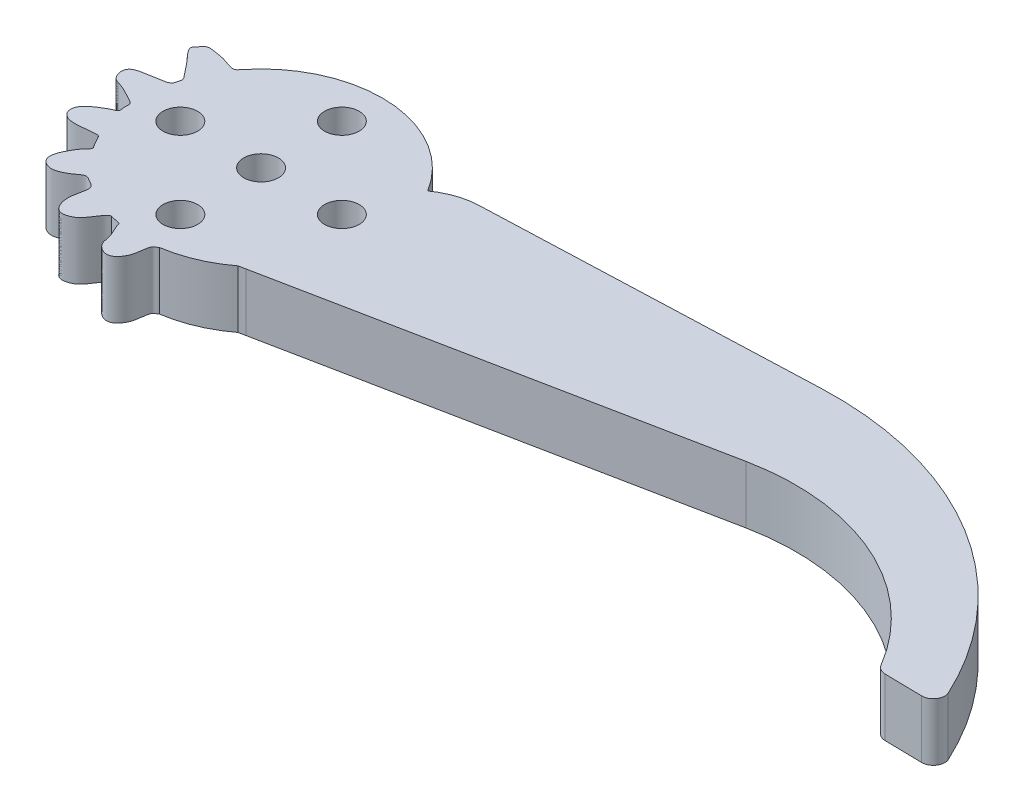
SolidWorks part; units mm, degrees
material "Thornel Mat VMA"
ref_plane "前视基准面" through (0, 0, 0) normal (0, 0, 1) x (1, 0, 0)
ref_plane "上视基准面" through (0, 0, 0) normal (0, 1, 0) x (1, 0, 0)
ref_plane "右视基准面" through (0, 0, 0) normal (1, 0, 0) x (0, 0, -1)
sketch "草图1" plane through (0, 0, 0) normal (0, 1, 0) x (1, 0, 0)
  line L0 (-21.0651, -6.9034) -> (15.0591, 0.323)
  line L1 (-39.2243, 6.1638) -> (-38.0931, 4.752)
  line L2 (-36.2478, 7.8215) -> (-36.3763, 7.6689)
  line L3 (12.8477, 9.059) -> (-15.7391, 7.9639)
  line L4 (37.0468, -9.61) -> (40.2704, -9.6677)
  arc A0 (-26.404, -9.0395) -> (-21.6294, -7.0162) centre (-27.9866, 1.3406) ccw
  arc A1 (-30.8811, -8.7526) -> (-29.9513, -8.974) centre (-27.9866, 1.3406) ccw
  arc A2 (-37.3561, -3.3988) -> (-36.7558, -4.4345) centre (-27.9866, 1.3406) ccw
  arc A3 (-38.0056, 4.4822) -> (-38.1702, 3.8986) centre (-27.9866, 1.3406) ccw
  arc A4 (-19.0327, 6.8249) -> (-36.2478, 7.8215) centre (-27.9866, 1.3406) ccw
  arc A5 (-15.7391, 7.9639) -> (-19.0327, 6.8249) centre (-15.5094, 1.9683) ccw
  arc A6 (41.2369, -8.3515) -> (12.8477, 9.059) centre (13.9962, -20.919) ccw
  arc A7 (40.2704, -9.6677) -> (41.2369, -8.3515) centre (40.2883, -8.6679) ccw
  arc A8 (36.2036, -9.1187) -> (37.0468, -9.61) centre (37.0647, -8.6102) ccw
  arc A9 (36.2036, -9.1187) -> (15.0591, 0.323) centre (18.9822, -19.2884) ccw
  ellipse E0 centre (-38.7365, 4.3843) end of major axis (-39.385, 4.0256) minor radius 0.7149 (-38.0056, 4.4822) -> (-38.0931, 4.752) ccw
  spline S0 degree 3 poles (-21.6294, -7.0162) (-21.4401, -6.9711) (-21.2528, -6.9333) (-21.0651, -6.9034) knots 0 0 0 0 1 1 1 1 weights 1 1 1 1
  spline S1 degree 3 poles (-29.9513, -8.974) (-29.9474, -9.0011) (-29.9366, -9.0585) (-29.9134, -9.15) (-29.8843, -9.245) (-29.8509, -9.3408) (-29.8138, -9.4371) (-29.7743, -9.5317) (-29.7328, -9.6252) (-29.6904, -9.7164) (-29.6478, -9.8051) (-29.6061, -9.8908) (-29.5656, -9.9745) (-29.5271, -10.0566) (-29.4927, -10.1347) (-29.4632, -10.2082) (-29.4382, -10.2778) (-29.4162, -10.3475) (-29.3964, -10.4191) (-29.3787, -10.4925) (-29.3607, -10.5762) (-29.3436, -10.6642) (-29.3261, -10.7549) (-29.309, -10.8384) (-29.2903, -10.9194) (-29.2689, -10.9978) (-29.244, -11.0736) (-29.2146, -11.1472) (-29.1798, -11.2185) (-29.1395, -11.2873) (-29.0934, -11.3536) (-29.0384, -11.4214) (-28.9661, -11.4975) (-28.8737, -11.5784) (-28.7599, -11.6594) (-28.6404, -11.7266) (-28.518, -11.7789) (-28.4, -11.8151) (-28.2935, -11.8345) (-28.1998, -11.8406) (-28.1193, -11.8375) (-28.0403, -11.8258) (-27.963, -11.8055) (-27.8815, -11.7747) (-27.7968, -11.7317) (-27.7101, -11.6755) (-27.625, -11.6083) (-27.5493, -11.5366) (-27.4832, -11.4636) (-27.4277, -11.3948) (-27.376, -11.3232) (-27.3259, -11.2467) (-27.2833, -11.1757) (-27.2476, -11.1119) (-27.2188, -11.0579) (-27.1921, -11.0048) (-27.1672, -10.9523) (-27.1443, -10.9) (-27.1231, -10.847) (-27.1014, -10.7865) (-27.0824, -10.7246) (-27.0654, -10.6594) (-27.0517, -10.5993) (-27.0385, -10.5338) (-27.0256, -10.4629) (-27.013, -10.3866) (-27.0005, -10.3055) (-26.988, -10.2202) (-26.975, -10.1284) (-26.9612, -10.0316) (-26.9466, -9.9318) (-26.9315, -9.8349) (-26.9158, -9.7422) (-26.8992, -9.6552) (-26.8817, -9.5749) (-26.8629, -9.5021) (-26.8428, -9.4373) (-26.821, -9.3808) (-26.7975, -9.3323) (-26.7718, -9.2916) (-26.7439, -9.2577) (-26.7135, -9.2296) (-26.6802, -9.206) (-26.6438, -9.1852) (-26.604, -9.1652) (-26.5606, -9.1436) (-26.5131, -9.1179) (-26.4613, -9.085) (-26.4237, -9.0562) (-26.404, -9.0395) knots 0 0 0 0 0.013505 0.02701 0.039991 0.053322 0.066303 0.079285 0.092266 0.105447 0.118428 0.131409 0.144391 0.157372 0.170353 0.181624 0.192111 0.202598 0.213086 0.223573 0.23406 0.248243 0.260115 0.271987 0.283859 0.295731 0.307654 0.319769 0.331885 0.344001 0.356116 0.368232 0.382792 0.402054 0.421317 0.443013 0.461451 0.47974 0.498046 0.510723 0.52339 0.536057 0.548724 0.56146 0.577383 0.593228 0.609073 0.626493 0.63938 0.65177 0.664159 0.676549 0.69008 0.699149 0.708218 0.717287 0.726355 0.735424 0.744493 0.753562 0.765524 0.773304 0.781085 0.788865 0.796646 0.804426 0.812207 0.819987 0.827768 0.836464 0.845107 0.853712 0.862317 0.870922 0.879527 0.888133 0.896738 0.905343 0.913948 0.922553 0.931159 0.939764 0.948369 0.956974 0.965579 0.974184 0.98279 0.991395 1 1 1 1 weights 1 1 1 1 1 1 1 1 1 1 1 1 1 1 1 1 1 1 1 1 1 1 1 1 1 1 1 1 1 1 1 1 1 1 1 1 1 1 1 1 1 1 1 1 1 1 1 1 1 1 1 1 1 1 1 1 1 1 1 1 1 1 1 1 1 1 1 1 1 1 1 1 1 1 1 1 1 1 1 1 1 1 1 1 1 1 1 1 1 1
  spline S2 degree 3 poles (-36.7558, -4.4345) (-36.7576, -4.4486) (-36.7635, -4.4864) (-36.7767, -4.54) (-36.7973, -4.5932) (-36.8227, -4.6397) (-36.8528, -4.682) (-36.8873, -4.7226) (-36.9259, -4.7636) (-36.9683, -4.8067) (-37.0141, -4.8535) (-37.063, -4.905) (-37.1145, -4.9622) (-37.1683, -5.0256) (-37.2238, -5.0953) (-37.2805, -5.1714) (-37.338, -5.2534) (-37.3963, -5.3416) (-37.4542, -5.4342) (-37.5123, -5.5317) (-37.5667, -5.6275) (-37.6169, -5.719) (-37.6617, -5.8029) (-37.7029, -5.8824) (-37.7412, -5.958) (-37.7763, -6.0296) (-37.8084, -6.0968) (-37.8374, -6.1601) (-37.8673, -6.2284) (-37.8944, -6.2949) (-37.9192, -6.3615) (-37.9396, -6.4218) (-37.9581, -6.4827) (-37.9749, -6.5449) (-37.99, -6.6096) (-38.0034, -6.6774) (-38.0151, -6.7524) (-38.0235, -6.833) (-38.0269, -6.9174) (-38.024, -6.9999) (-38.0143, -7.08) (-37.9963, -7.1615) (-37.9678, -7.2447) (-37.9265, -7.3286) (-37.8735, -7.4082) (-37.8116, -7.4801) (-37.7428, -7.544) (-37.6692, -7.6) (-37.5899, -7.6499) (-37.5038, -7.6949) (-37.4219, -7.7299) (-37.3467, -7.7566) (-37.2814, -7.7761) (-37.2167, -7.7916) (-37.1525, -7.8031) (-37.0886, -7.8105) (-37.0244, -7.8135) (-36.9589, -7.8121) (-36.8913, -7.8061) (-36.8204, -7.7955) (-36.7454, -7.7801) (-36.6652, -7.7598) (-36.579, -7.7342) (-36.4863, -7.7028) (-36.3891, -7.666) (-36.2887, -7.6238) (-36.1869, -7.5767) (-36.0837, -7.5241) (-35.9804, -7.4666) (-35.8778, -7.4046) (-35.7769, -7.3392) (-35.6785, -7.2715) (-35.5816, -7.2018) (-35.4924, -7.1358) (-35.4111, -7.0757) (-35.3392, -7.0235) (-35.2718, -6.977) (-35.209, -6.9369) (-35.1503, -6.904) (-35.0955, -6.8787) (-35.0438, -6.8612) (-34.9937, -6.8514) (-34.9445, -6.8495) (-34.895, -6.855) (-34.8447, -6.8671) (-34.7928, -6.8851) (-34.7385, -6.9083) (-34.6817, -6.9358) (-34.6225, -6.9669) (-34.5565, -7.0034) (-34.4879, -7.0427) (-34.4182, -7.0834) (-34.3535, -7.1217) (-34.2909, -7.1594) (-34.2313, -7.1961) (-34.1748, -7.2321) (-34.1181, -7.2704) (-34.0632, -7.3116) (-34.0122, -7.3566) (-33.9693, -7.4047) (-33.9348, -7.4579) (-33.9084, -7.5201) (-33.8935, -7.5846) (-33.8866, -7.65) (-33.8848, -7.71) (-33.8867, -7.7764) (-33.8922, -7.8492) (-33.9008, -7.928) (-33.9123, -8.0122) (-33.9263, -8.1009) (-33.9423, -8.1941) (-33.9598, -8.2887) (-33.9776, -8.3821) (-33.995, -8.4713) (-34.0117, -8.5566) (-34.0276, -8.6378) (-34.0421, -8.7141) (-34.0552, -8.7852) (-34.0666, -8.8511) (-34.0762, -8.912) (-34.0848, -8.9725) (-34.0918, -9.0325) (-34.0973, -9.0933) (-34.1009, -9.1527) (-34.1028, -9.2124) (-34.1031, -9.2732) (-34.1019, -9.3348) (-34.0991, -9.3973) (-34.0948, -9.4623) (-34.0878, -9.5378) (-34.077, -9.6234) (-34.0612, -9.7164) (-34.0412, -9.8085) (-34.0157, -9.9034) (-33.9845, -9.9985) (-33.9476, -10.0934) (-33.9065, -10.1836) (-33.846, -10.2982) (-33.7766, -10.4025) (-33.6975, -10.4917) (-33.6337, -10.5499) (-33.5645, -10.5998) (-33.4818, -10.6453) (-33.384, -10.6818) (-33.2706, -10.7046) (-33.1624, -10.71) (-33.0633, -10.7035) (-32.975, -10.6901) (-32.8872, -10.6701) (-32.7765, -10.6374) (-32.6747, -10.5991) (-32.5844, -10.5603) (-32.5245, -10.5327) (-32.4666, -10.504) (-32.4106, -10.4741) (-32.3563, -10.4424) (-32.303, -10.4082) (-32.2521, -10.3718) (-32.2028, -10.3325) (-32.1545, -10.2901) (-32.1052, -10.2426) (-32.0543, -10.1896) (-32.002, -10.1311) (-31.9482, -10.0674) (-31.8933, -9.999) (-31.8373, -9.9262) (-31.7779, -9.8464) (-31.7171, -9.7619) (-31.6562, -9.6749) (-31.5986, -9.5907) (-31.5441, -9.5094) (-31.493, -9.432) (-31.4454, -9.3593) (-31.4014, -9.2918) (-31.3608, -9.2298) (-31.323, -9.1735) (-31.2877, -9.1225) (-31.2539, -9.0766) (-31.2208, -9.0349) (-31.187, -8.9966) (-31.1514, -8.9604) (-31.1123, -8.9251) (-31.068, -8.8888) (-31.0165, -8.8498) (-30.9558, -8.8057) (-30.9075, -8.7714) (-30.8811, -8.7526) knots 0 0 0 0 0.002778 0.007862 0.012946 0.018029 0.023113 0.028197 0.033281 0.038364 0.043448 0.048532 0.053616 0.058699 0.063783 0.068867 0.073951 0.079034 0.084303 0.089387 0.094817 0.099601 0.104161 0.108722 0.113282 0.117843 0.122403 0.126964 0.131525 0.138037 0.143059 0.148081 0.153103 0.158125 0.163226 0.168491 0.173927 0.18039 0.186853 0.193317 0.19978 0.206244 0.213841 0.221742 0.229642 0.237543 0.244782 0.251868 0.258955 0.266041 0.273652 0.278927 0.284202 0.289478 0.294753 0.300028 0.305304 0.310582 0.315857 0.321062 0.326266 0.33147 0.336732 0.342077 0.347506 0.352711 0.357947 0.363147 0.368347 0.373547 0.378746 0.383946 0.389146 0.394691 0.399336 0.403973 0.40861 0.413247 0.417884 0.422521 0.427158 0.431795 0.436645 0.441436 0.446178 0.45092 0.455662 0.460404 0.465146 0.469889 0.475767 0.48079 0.485812 0.490834 0.495856 0.500878 0.506033 0.512297 0.518561 0.524826 0.53109 0.537354 0.54408 0.548169 0.552258 0.556347 0.560435 0.564524 0.568613 0.572702 0.576791 0.58107 0.585125 0.589104 0.593083 0.597062 0.601041 0.60502 0.608999 0.612978 0.616957 0.621815 0.626643 0.631577 0.63655 0.641562 0.646614 0.651441 0.656269 0.661506 0.668358 0.675169 0.68198 0.688791 0.696572 0.70396 0.711346 0.718732 0.733327 0.740483 0.74764 0.754797 0.762088 0.771803 0.781518 0.791234 0.7983 0.805029 0.811754 0.818479 0.830366 0.835343 0.840319 0.845296 0.850272 0.855249 0.860225 0.86521 0.869689 0.874145 0.8786 0.883056 0.887511 0.891966 0.896422 0.900877 0.905399 0.9106 0.915567 0.920534 0.9255 0.930467 0.935434 0.9404 0.945367 0.950334 0.9553 0.960267 0.965233 0.9702 0.975167 0.980133 0.9851 0.990067 0.995033 1 1 1 1 weights 1 1 1 1 1 1 1 1 1 1 1 1 1 1 1 1 1 1 1 1 1 1 1 1 1 1 1 1 1 1 1 1 1 1 1 1 1 1 1 1 1 1 1 1 1 1 1 1 1 1 1 1 1 1 1 1 1 1 1 1 1 1 1 1 1 1 1 1 1 1 1 1 1 1 1 1 1 1 1 1 1 1 1 1 1 1 1 1 1 1 1 1 1 1 1 1 1 1 1 1 1 1 1 1 1 1 1 1 1 1 1 1 1 1 1 1 1 1 1 1 1 1 1 1 1 1 1 1 1 1 1 1 1 1 1 1 1 1 1 1 1 1 1 1 1 1 1 1 1 1 1 1 1 1 1 1 1 1 1 1 1 1 1 1 1 1 1 1 1 1 1 1 1 1 1 1 1 1 1 1 1 1 1 1 1 1 1
  spline S3 degree 3 poles (-40.631, 1.5824) (-40.5898, 1.5698) (-40.4741, 1.5327) (-40.2983, 1.4702) (-40.1114, 1.3956) (-39.9434, 1.3219) (-39.7918, 1.2501) (-39.6543, 1.181) (-39.5287, 1.1153) (-39.4135, 1.0534) (-39.3069, 0.9957) (-39.2077, 0.9423) (-39.115, 0.8929) (-39.0278, 0.8474) (-38.9456, 0.8054) (-38.8682, 0.766) (-38.7954, 0.7285) (-38.7268, 0.6914) (-38.6659, 0.6553) (-38.6135, 0.6192) (-38.5697, 0.5832) (-38.5324, 0.5449) (-38.5012, 0.5037) (-38.4784, 0.4625) (-38.4635, 0.4234) (-38.4547, 0.3873) (-38.4501, 0.3511) (-38.4493, 0.3137) (-38.4516, 0.2747) (-38.456, 0.2339) (-38.4613, 0.1922) (-38.4659, 0.1504) (-38.4688, 0.1088) (-38.47, 0.0653) (-38.4691, 0.019) (-38.466, -0.0301) (-38.4609, -0.0814) (-38.4541, -0.1344) (-38.4459, -0.1903) (-38.4373, -0.2472) (-38.4297, -0.3027) (-38.4244, -0.3538) (-38.422, -0.4005) (-38.423, -0.4429) (-38.4279, -0.4807) (-38.4369, -0.5139) (-38.4501, -0.5427) (-38.4702, -0.571) (-38.4982, -0.5964) (-38.5346, -0.6195) (-38.5749, -0.6394) (-38.6191, -0.6581) (-38.6666, -0.6769) (-38.7168, -0.6968) (-38.7724, -0.7195) (-38.8359, -0.747) (-38.9081, -0.7804) (-38.9864, -0.8192) (-39.0679, -0.8621) (-39.1801, -0.9244) (-39.2954, -0.9926) (-39.4104, -1.0629) (-39.495, -1.1157) (-39.5789, -1.1689) (-39.6617, -1.2226) (-39.7569, -1.2863) (-39.8477, -1.3501) (-39.9353, -1.4161) (-40.0062, -1.4727) (-40.076, -1.5319) (-40.1433, -1.5925) (-40.2084, -1.655) (-40.2748, -1.7227) (-40.3346, -1.7882) (-40.3871, -1.8499) (-40.4297, -1.9036) (-40.4675, -1.9552) (-40.5004, -2.0046) (-40.5284, -2.0519) (-40.5549, -2.1032) (-40.5763, -2.1533) (-40.5936, -2.2039) (-40.6067, -2.2502) (-40.6176, -2.2974) (-40.6264, -2.3459) (-40.6339, -2.399) (-40.6392, -2.4576) (-40.6411, -2.521) (-40.6385, -2.5847) (-40.631, -2.6473) (-40.6166, -2.7175) (-40.5922, -2.7951) (-40.551, -2.8858) (-40.5021, -2.9626) (-40.45, -3.0258) (-40.4059, -3.0714) (-40.3574, -3.115) (-40.3092, -3.153) (-40.2632, -3.1859) (-40.2208, -3.2138) (-40.1781, -3.2396) (-40.1349, -3.2634) (-40.0761, -3.2925) (-40.0141, -3.3175) (-39.9448, -3.3388) (-39.8893, -3.353) (-39.8289, -3.3655) (-39.7637, -3.3764) (-39.694, -3.3857) (-39.6146, -3.3937) (-39.5295, -3.3997) (-39.4405, -3.4032) (-39.355, -3.4043) (-39.2697, -3.403) (-39.1848, -3.3996) (-39.1007, -3.3941) (-39.017, -3.387) (-38.932, -3.3784) (-38.8466, -3.3688) (-38.7597, -3.3589) (-38.6722, -3.3491) (-38.5817, -3.3396) (-38.4885, -3.3304) (-38.3929, -3.3219) (-38.2656, -3.3114) (-38.1383, -3.3019) (-38.019, -3.2929) (-37.9338, -3.2863) (-37.8557, -3.2801) (-37.7841, -3.2745) (-37.7191, -3.2698) (-37.661, -3.2665) (-37.6095, -3.2654) (-37.5641, -3.2671) (-37.5241, -3.2726) (-37.4883, -3.2828) (-37.4555, -3.299) (-37.424, -3.3224) (-37.3919, -3.3545) (-37.3686, -3.3828) (-37.3561, -3.3988) knots 0 0 0 0 0.004714 0.013662 0.022611 0.031559 0.040507 0.049455 0.058404 0.067352 0.0763 0.085248 0.094197 0.103145 0.112093 0.121041 0.12999 0.138938 0.148201 0.156222 0.163851 0.17148 0.179109 0.186738 0.192792 0.198369 0.203946 0.209523 0.2151 0.220676 0.226253 0.231142 0.23566 0.240179 0.244698 0.249217 0.253735 0.258254 0.262773 0.267807 0.272633 0.277271 0.28191 0.286548 0.291186 0.295825 0.30052 0.30529 0.31209 0.318465 0.32484 0.331215 0.33759 0.343965 0.35034 0.357735 0.365908 0.374082 0.382255 0.390428 0.406729 0.414629 0.422528 0.430428 0.438327 0.446227 0.458082 0.465174 0.472557 0.479649 0.48674 0.493832 0.500923 0.509402 0.515713 0.522025 0.528336 0.534648 0.540959 0.547271 0.555957 0.562514 0.56907 0.575627 0.582183 0.588739 0.596673 0.604935 0.613197 0.621459 0.629755 0.641751 0.654218 0.670112 0.678364 0.686617 0.69487 0.703472 0.710127 0.716723 0.72332 0.729917 0.736514 0.749651 0.755997 0.762343 0.768689 0.775035 0.781381 0.787727 0.795508 0.802346 0.809109 0.815872 0.822635 0.829398 0.83616 0.842923 0.850045 0.856738 0.863484 0.870284 0.877136 0.884043 0.891004 0.904506 0.911628 0.918426 0.925224 0.932022 0.93882 0.945617 0.952415 0.959213 0.966011 0.972809 0.979607 0.986404 0.993202 1 1 1 1 weights 1 1 1 1 1 1 1 1 1 1 1 1 1 1 1 1 1 1 1 1 1 1 1 1 1 1 1 1 1 1 1 1 1 1 1 1 1 1 1 1 1 1 1 1 1 1 1 1 1 1 1 1 1 1 1 1 1 1 1 1 1 1 1 1 1 1 1 1 1 1 1 1 1 1 1 1 1 1 1 1 1 1 1 1 1 1 1 1 1 1 1 1 1 1 1 1 1 1 1 1 1 1 1 1 1 1 1 1 1 1 1 1 1 1 1 1 1 1 1 1 1 1 1 1 1 1 1 1 1 1 1 1 1 1 1 1 1 1 1 1 1
  spline S4 degree 3 poles (-38.1702, 3.8986) (-38.179, 3.8905) (-38.2039, 3.8676) (-38.2422, 3.8338) (-38.2856, 3.7992) (-38.3289, 3.7692) (-38.3741, 3.7428) (-38.4229, 3.7193) (-38.4766, 3.698) (-38.5363, 3.6783) (-38.6028, 3.6595) (-38.6766, 3.6414) (-38.7577, 3.6235) (-38.8462, 3.6057) (-38.9416, 3.5878) (-39.049, 3.5687) (-39.1712, 3.548) (-39.3078, 3.5259) (-39.4506, 3.5036) (-39.5934, 3.4817) (-39.7181, 3.4628) (-39.8228, 3.4468) (-39.9087, 3.4334) (-39.9895, 3.4206) (-40.0652, 3.4082) (-40.1356, 3.3961) (-40.2012, 3.3843) (-40.2651, 3.3721) (-40.3271, 3.3595) (-40.3875, 3.3463) (-40.4459, 3.3327) (-40.5028, 3.3185) (-40.5593, 3.3035) (-40.6177, 3.287) (-40.6813, 3.2675) (-40.7488, 3.2446) (-40.8162, 3.2186) (-40.8804, 3.1899) (-40.9446, 3.1564) (-41.0074, 3.1168) (-41.0674, 3.07) (-41.1207, 3.0181) (-41.1661, 2.9619) (-41.2035, 2.902) (-41.2342, 2.8368) (-41.262, 2.754) (-41.2816, 2.6525) (-41.2883, 2.5347) (-41.2814, 2.4164) (-41.2609, 2.292) (-41.2251, 2.1641) (-41.1704, 2.0311) (-41.0972, 1.9028) (-41.0041, 1.7853) (-40.894, 1.6878) (-40.7695, 1.6165) (-40.6783, 1.5898) (-40.631, 1.5824) knots 0 0 0 0 0.007377 0.021666 0.035955 0.050243 0.064532 0.07882 0.093109 0.107397 0.121686 0.135974 0.150263 0.164551 0.17884 0.193153 0.209869 0.227751 0.245632 0.263514 0.281396 0.293514 0.305493 0.317471 0.32945 0.341429 0.353408 0.365386 0.378929 0.392061 0.404708 0.417763 0.430244 0.442726 0.457007 0.47317 0.489235 0.505299 0.521599 0.540785 0.559801 0.578817 0.597589 0.615343 0.633097 0.652436 0.680707 0.708146 0.735415 0.762004 0.793533 0.824827 0.859021 0.894299 0.929533 0.964766 1 1 1 1 weights 1 1 1 1 1 1 1 1 1 1 1 1 1 1 1 1 1 1 1 1 1 1 1 1 1 1 1 1 1 1 1 1 1 1 1 1 1 1 1 1 1 1 1 1 1 1 1 1 1 1 1 1 1 1 1 1 1 1
  spline S5 degree 3 poles (-36.3763, 7.6689) (-36.3877, 7.659) (-36.4091, 7.6411) (-36.4388, 7.6188) (-36.4687, 7.6002) (-36.5006, 7.5852) (-36.5363, 7.5735) (-36.5772, 7.5652) (-36.6246, 7.5605) (-36.6794, 7.5599) (-36.7393, 7.5639) (-36.8014, 7.5723) (-36.8641, 7.5842) (-36.9302, 7.6) (-37.0023, 7.6203) (-37.079, 7.6445) (-37.1596, 7.6722) (-37.2485, 7.7043) (-37.3383, 7.7378) (-37.427, 7.7708) (-37.507, 7.7997) (-37.5855, 7.8269) (-37.6623, 7.8519) (-37.7371, 7.8744) (-37.8101, 7.8942) (-37.8816, 7.9116) (-37.9539, 7.9272) (-38.0259, 7.941) (-38.0989, 7.9538) (-38.1725, 7.9661) (-38.2484, 7.9786) (-38.3269, 7.9916) (-38.4072, 8.005) (-38.4896, 8.0191) (-38.5738, 8.0337) (-38.6589, 8.0486) (-38.7441, 8.0633) (-38.8279, 8.0773) (-38.9086, 8.0897) (-38.9848, 8.1002) (-39.0559, 8.1082) (-39.1214, 8.1134) (-39.1809, 8.1155) (-39.2347, 8.1143) (-39.2912, 8.109) (-39.3546, 8.0957) (-39.4212, 8.069) (-39.487, 8.0266) (-39.5403, 7.981) (-39.584, 7.9393) (-39.6166, 7.907) (-39.651, 7.8717) (-39.6877, 7.8337) (-39.7255, 7.7941) (-39.7636, 7.7539) (-39.8001, 7.7153) (-39.8341, 7.6793) (-39.8646, 7.6465) (-39.8922, 7.6166) (-39.9169, 7.5891) (-39.9387, 7.5643) (-39.9582, 7.5409) (-39.9757, 7.5186) (-39.9912, 7.4967) (-40.0049, 7.475) (-40.0168, 7.4532) (-40.0274, 7.4307) (-40.0374, 7.4053) (-40.0459, 7.3772) (-40.0518, 7.3466) (-40.0544, 7.316) (-40.0538, 7.2856) (-40.0507, 7.2557) (-40.0454, 7.2265) (-40.038, 7.1971) (-40.0277, 7.1652) (-40.0136, 7.1301) (-39.9941, 7.0903) (-39.9697, 7.0471) (-39.9397, 6.9993) (-39.9039, 6.9466) (-39.862, 6.8887) (-39.8142, 6.8256) (-39.7608, 6.7577) (-39.7023, 6.6856) (-39.6392, 6.61) (-39.5723, 6.5321) (-39.5027, 6.4531) (-39.4316, 6.3747) (-39.3603, 6.2986) (-39.2903, 6.227) (-39.2458, 6.1838) (-39.2243, 6.1638) knots 0 0 0 0 0.013765 0.027529 0.041008 0.054678 0.068157 0.081635 0.095114 0.108702 0.122181 0.133657 0.144209 0.15476 0.165312 0.176332 0.186884 0.197435 0.210598 0.220722 0.230847 0.240972 0.251096 0.261221 0.271346 0.281471 0.291595 0.302512 0.312594 0.322678 0.333087 0.343168 0.35325 0.363332 0.373413 0.383495 0.393668 0.40389 0.414112 0.424334 0.434556 0.444778 0.455 0.465222 0.475444 0.490781 0.510911 0.53104 0.551169 0.560176 0.569091 0.578124 0.587301 0.596623 0.605504 0.614474 0.622865 0.63085 0.638835 0.64682 0.654805 0.66279 0.671573 0.680657 0.689605 0.698553 0.707501 0.71645 0.727822 0.738724 0.749626 0.760768 0.771314 0.781859 0.792404 0.80295 0.815695 0.827982 0.840269 0.852556 0.864843 0.87713 0.889417 0.901704 0.913991 0.926278 0.938565 0.950852 0.963139 0.975426 0.987713 1 1 1 1 weights 1 1 1 1 1 1 1 1 1 1 1 1 1 1 1 1 1 1 1 1 1 1 1 1 1 1 1 1 1 1 1 1 1 1 1 1 1 1 1 1 1 1 1 1 1 1 1 1 1 1 1 1 1 1 1 1 1 1 1 1 1 1 1 1 1 1 1 1 1 1 1 1 1 1 1 1 1 1 1 1 1 1 1 1 1 1 1 1 1 1 1 1 1
extrude "凸台-拉伸1" add sketch "草图1" along normal blind 5
sketch "草图3" plane through (0, 5, 0) normal (0, 1, 0) x (1, 0, 0)
  line L0 (-27.9866, 1.3406) -> (-27.9866, 13.4992) construction
  line L1 (-27.9866, 1.3406) -> (-14.4459, 1.3406) construction
  circle A0 centre (-27.9866, 1.3406) radius 7 construction
  circle A1 centre (-27.9866, 8.3406) radius 1.5
  circle A2 centre (-20.9866, 1.3406) radius 1.5
  circle A3 centre (-27.9866, -5.6594) radius 1.5
  circle A4 centre (-34.9866, 1.3406) radius 1.5
  circle A5 centre (-27.9866, 1.3406) radius 1.5
  dimension "D1" = 14
  dimension "D2" = 3
  dimension "D3" = 3
  dimension "D4" = 3
extrude "切除-拉伸1" cut sketch "草图3" against normal blind 10
